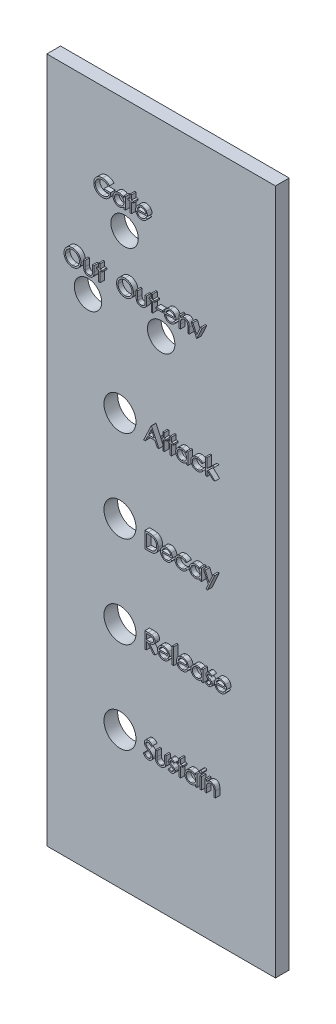
SolidWorks part; units mm, degrees
ref_plane "Front Plane" through (0, 0, 0) normal (0, 0, 1) x (1, 0, 0)
ref_plane "Top Plane" through (0, 0, 0) normal (0, 1, 0) x (1, 0, 0)
ref_plane "Right Plane" through (0, 0, 0) normal (1, 0, 0) x (0, 0, -1)
sketch "Sketch1" plane through (0, 0, 0) normal (0, 0, 1) x (1, 0, 0)
  line L0 (-25, 34) -> (25, 34) construction
  line L1 (-25, -75) -> (25, -75)
  line L2 (-25, -75) -> (-25, 75)
  line L3 (-25, 75) -> (25, 75)
  line L4 (25, -75) -> (25, 75)
  line L5 (-25, -75) -> (25, 75) construction
  line L6 (-25, 75) -> (25, -75) construction
  line L7 (-9, 75) -> (-9, -75) construction
  line L8 (-16, 34) -> (0, 34) construction
  circle A0 centre (-16, 34) radius 3
  circle A1 centre (0, 34) radius 3
  circle A3 centre (-9, -45) radius 3.5
  circle A4 centre (-9, -25) radius 3.5
  circle A5 centre (-9, -5) radius 3.5
  circle A6 centre (-9, 15) radius 3.5
  circle A7 centre (-8, 50) radius 3
  point P0 (0, 0)
  point P26 (0, 75)
  dimension "D4" = 16
  dimension "D7" = 6
  dimension "D9" = 7
  dimension "D1" = 150
  dimension "D2" = 50
  dimension "D3" = 25
  dimension "D5" = 16
  dimension "D6" = 8
  dimension "D8" = 16
  dimension "D10" = 20
  dimension "D11" = 20
  dimension "D12" = 20
  dimension "D13" = 30
extrude "Boss-Extrude1" add sketch "Sketch1" along normal blind 3
sketch "Sketch2" plane through (0, 0, 3) normal (0, 0, 1) x (1, 0, 0)
  line L0 (25, 75) -> (-25, 75) construction
  line L1 (-25, 75) -> (-25, -75) construction
  line L2 (-25, -75) -> (25, -75) construction
  text T0 "Gate"
  text T1 "Out  Out-env"
  text T2 "Attack\r\n\r\n\r\nDecay" font "Century Gothic" height 3.5
  text T3 "Release\r\n\r\n\r\nSustain"
  point P4 (0, 0)
  point P5 (-5.5846, 56.7414)
  point P9 (-0.4455, 39.3671)
  dimension "D1" = 20
  dimension "D2" = 11
  dimension "D3" = 36.5
  dimension "D4" = 22
  dimension "4.5" = 4.5
  dimension "D5" = 88.5
  dimension "D6" = 22
  dimension "D7" = 49
extrude "Boss-Extrude2" add sketch "Sketch2" along normal blind 1
